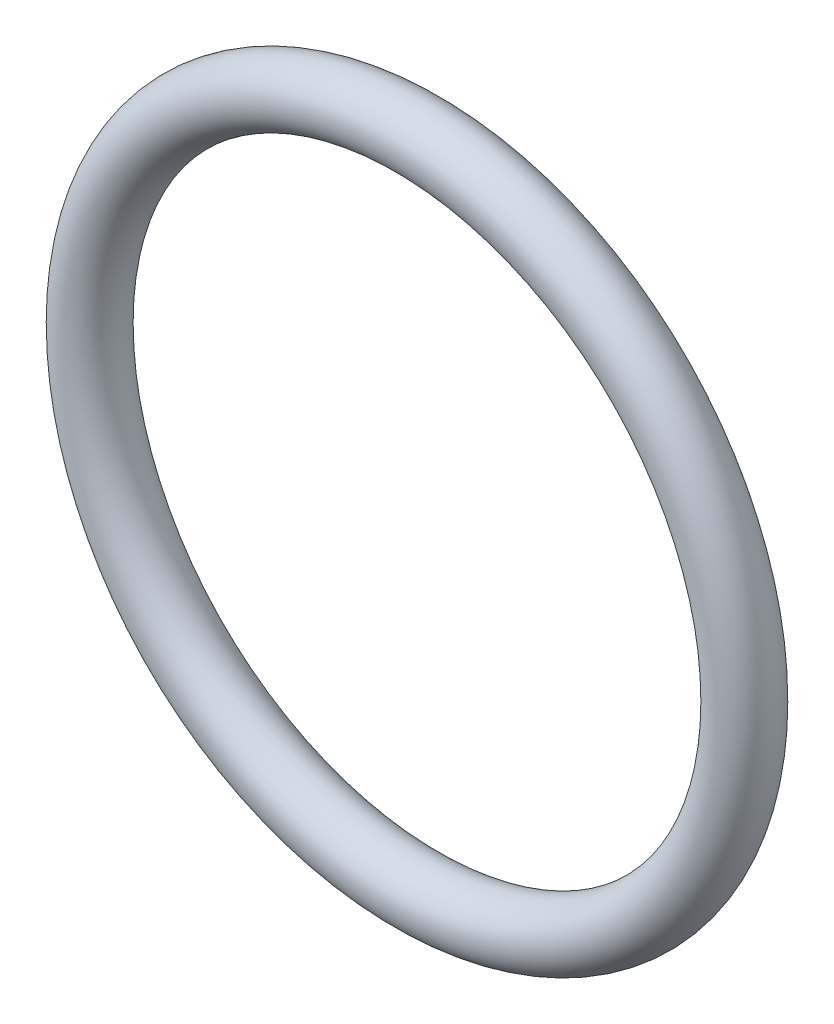
SolidWorks part; units mm, degrees
ref_plane "Front Plane" through (0, 0, 0) normal (0, 0, 1) x (1, 0, 0)
ref_plane "Top Plane" through (0, 0, 0) normal (0, 1, 0) x (1, 0, 0)
ref_plane "Right Plane" through (0, 0, 0) normal (1, 0, 0) x (0, 0, -1)
sketch "Sketch1" plane through (0, 0, 0) normal (1, 0, 0) x (0, 0, -1)
  line L0 (0, 0) -> (13.7118, 0) construction
  line L1 (0, 10.365) -> (0, 8.585) construction
  circle A0 centre (0, 9.475) radius 0.89
  dimension "D1" = 1.78
  dimension "D2" = 8.585
revolve "Revolve1" add sketch "Sketch1" angle 360 about L0
sketch "Sketch2" plane through (0, 0, 0) normal (0, 0, 1) x (1, 0, 0)
  circle A0 centre (0, 0) radius 9 construction
  dimension "D1" = 18
